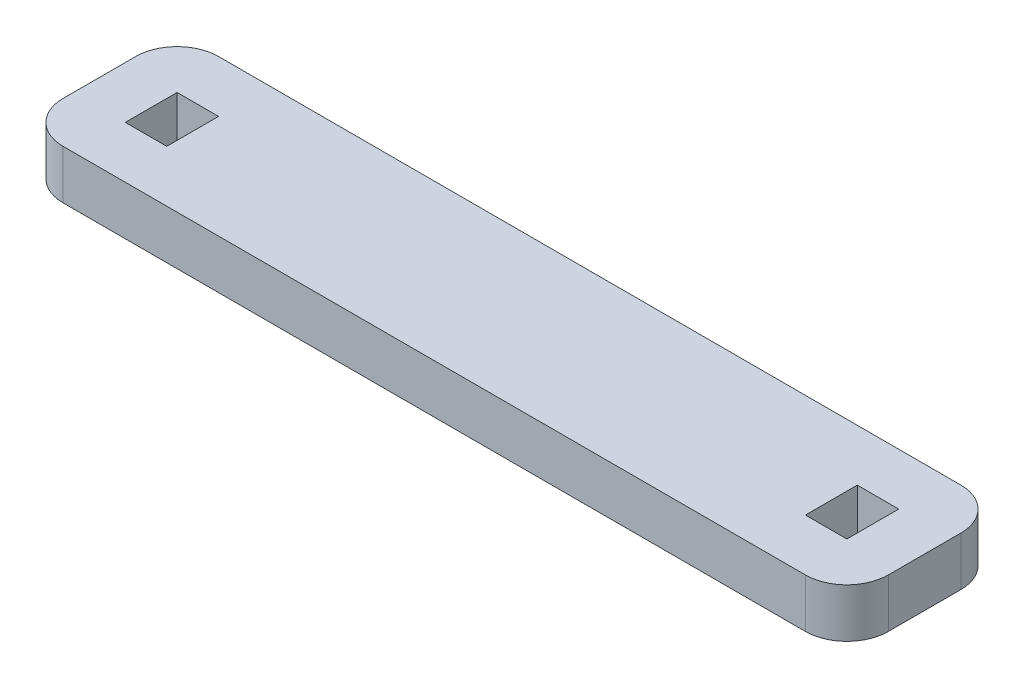
SolidWorks part; units mm, degrees
ref_plane "Front Plane" through (0, 0, 0) normal (0, 0, 1) x (1, 0, 0)
ref_plane "Top Plane" through (0, 0, 0) normal (0, 1, 0) x (1, 0, 0)
ref_plane "Right Plane" through (0, 0, 0) normal (1, 0, 0) x (0, 0, -1)
sketch "Sketch1" plane through (0, 0, 0) normal (0, 1, 0) x (1, 0, 0)
  line L0 (-20.828, 0) -> (20.828, 0) construction
  line L6 (25.273, -4.7625) -> (-25.273, -4.7625)
  line L7 (-19.558, -1.5875) -> (-22.098, -1.5875)
  line L8 (-19.558, -1.5875) -> (-19.558, 1.5875)
  line L9 (-19.558, 1.5875) -> (-22.098, 1.5875)
  line L10 (-22.098, -1.5875) -> (-22.098, 1.5875)
  line L11 (-19.558, -1.5875) -> (-22.098, 1.5875) construction
  line L12 (-19.558, 1.5875) -> (-22.098, -1.5875) construction
  line L13 (22.098, -1.5875) -> (19.558, -1.5875)
  line L14 (22.098, -1.5875) -> (22.098, 1.5875)
  line L15 (22.098, 1.5875) -> (19.558, 1.5875)
  line L16 (19.558, -1.5875) -> (19.558, 1.5875)
  line L17 (22.098, -1.5875) -> (19.558, 1.5875) construction
  line L18 (22.098, 1.5875) -> (19.558, -1.5875) construction
  line L19 (25.273, -4.7625) -> (25.273, 4.7625)
  line L20 (25.273, 4.7625) -> (-25.273, 4.7625)
  line L21 (-25.273, -4.7625) -> (-25.273, 4.7625)
  line L22 (25.273, -4.7625) -> (-25.273, 4.7625) construction
  line L23 (25.273, 4.7625) -> (-25.273, -4.7625) construction
  point P0 (0, 0)
  point P1 (0, 0)
  point P6 (-20.828, 0)
  point P11 (20.828, 0)
  dimension "D1" = 9.525
  dimension "D2" = 3.175
  dimension "D3" = 2.54
  dimension "D4" = 41.656
  dimension "D5" = 3.175
extrude "Boss-Extrude1" add sketch "Sketch1" along normal mid plane 3
fillet "Fillet1" radius 2.54 4 edges at (-25.273, 0, -4.7625) (25.273, 0, -4.7625) (25.273, 0, 4.7625) (-25.273, 0, 4.7625)
